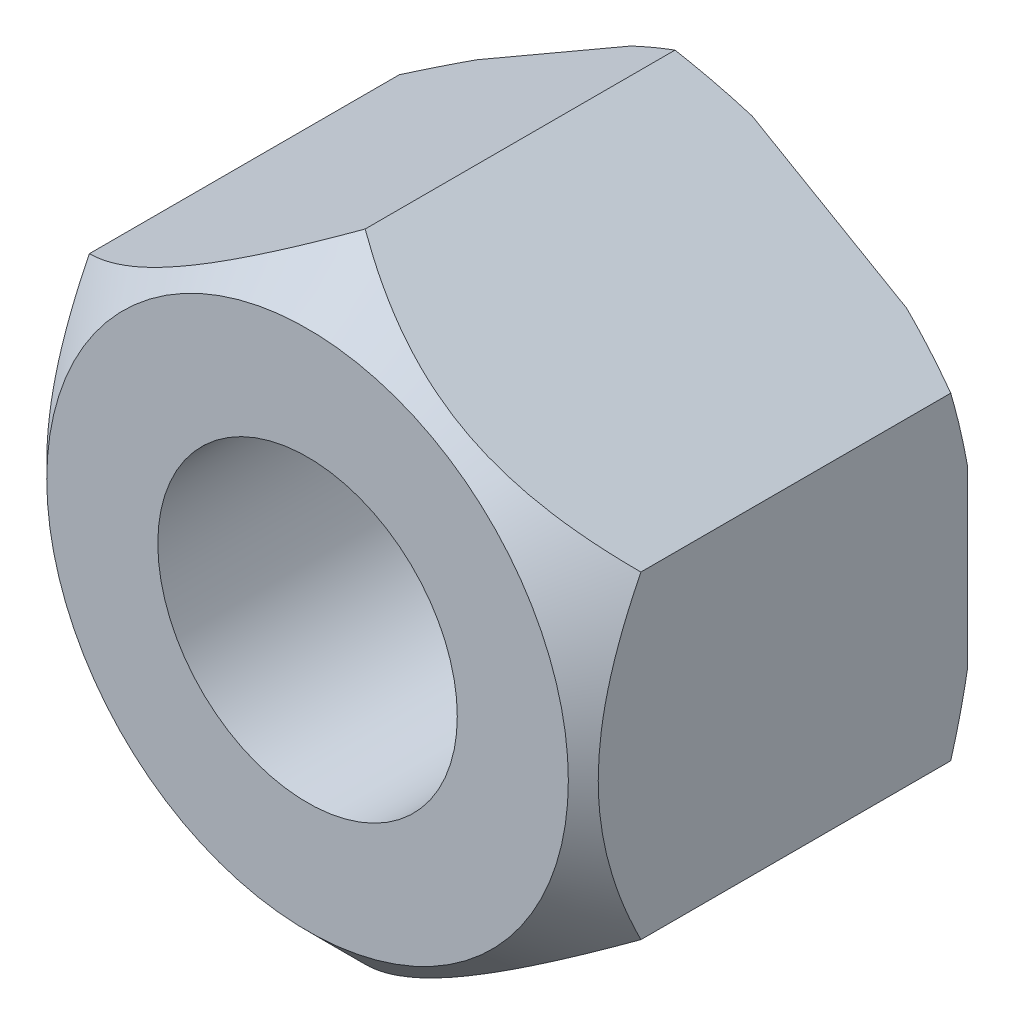
SolidWorks part; units mm, degrees
ref_plane "基准面1" through (0, 0, 0) normal (0, 0, 1) x (1, 0, 0)
ref_plane "基准面2" through (0, 0, 0) normal (0, 1, 0) x (1, 0, 0)
ref_plane "基准面3" through (0, 0, 0) normal (1, 0, 0) x (0, 0, -1)
sketch "尺寸草图" plane through (0, 0, 0) normal (0, 0, 1) x (1, 0, 0)
  line L0 (0, 0) -> (12.63, 0)
  line L1 (0, 0) -> (5.75, 0)
  line L2 (5.75, 0) -> (12.63, 0)
  line L3 (-4.7619, 0) -> (0, 0)
  point P3 (5, 0)
  point P4 (0.8, 0)
  point P5 (8.79, 0)
  point P7 (3.84, 0)
  point P8 (8, 0)
  point P15 (11.05, 0)
  dimension "D1" = 4.7619
  dimension "D" = 5
  dimension "P" = 0.8
  dimension "e(min)" = 8.79
  dimension "mw(min)" = 3.84
  dimension "s(max)" = 8
  dimension "da(max)" = 5.75
  dimension "dw(min)" = 6.88
  dimension "h(max)" = 5.3
sketch "草图1" plane through (0, 0, 0) normal (0, 0, 1) x (1, 0, 0)
  line L0 (-3.8062, 0) -> (3.8062, 0) construction
  line L1 (0, 4.395) -> (0, -4.395) construction
  line L3 (0, 4.395) -> (-3.8062, 2.1975)
  line L4 (-3.8062, 2.1975) -> (-3.8062, -2.1975)
  line L5 (-3.8062, -2.1975) -> (0, -4.395)
  line L6 (0, -4.395) -> (3.8062, -2.1975)
  line L7 (3.8062, -2.1975) -> (3.8062, 2.1975)
  line L8 (3.8062, 2.1975) -> (0, 4.395)
  circle A0 centre (0, 0) radius 3.8062 construction
  circle A1 centre (0, 0) radius 2.067
  dimension "D" = 4.134
  dimension "e" = 8.79
extrude "基体-拉伸" add sketch "草图1" along normal blind 5.3
cosmetic thread "装饰螺纹线1" parameters "D2"=5
sketch "草图2" plane through (0, 0, 0) normal (0, 0, -1) x (-1, 0, 0)
  circle A0 centre (0, 0) radius 4
  circle A1 centre (0, 0) radius 2.067 construction
  dimension "s" = 8
extrude "切除-拉伸1" cut sketch "草图2" against normal through all draft 60 flip side to cut
chamfer "倒角1" distance 0.1235 angle 45 1 edges at (2.067, 0, 0)
sketch "草图9" plane through (0, 0, 5.3) normal (0, 0, 1) x (1, 0, 0)
  circle A0 centre (0, 0) radius 3.6
  dimension "s*0.9" = 7.2
extrude "切除-拉伸7" cut sketch "草图9" against normal through all draft 45 flip side to cut
